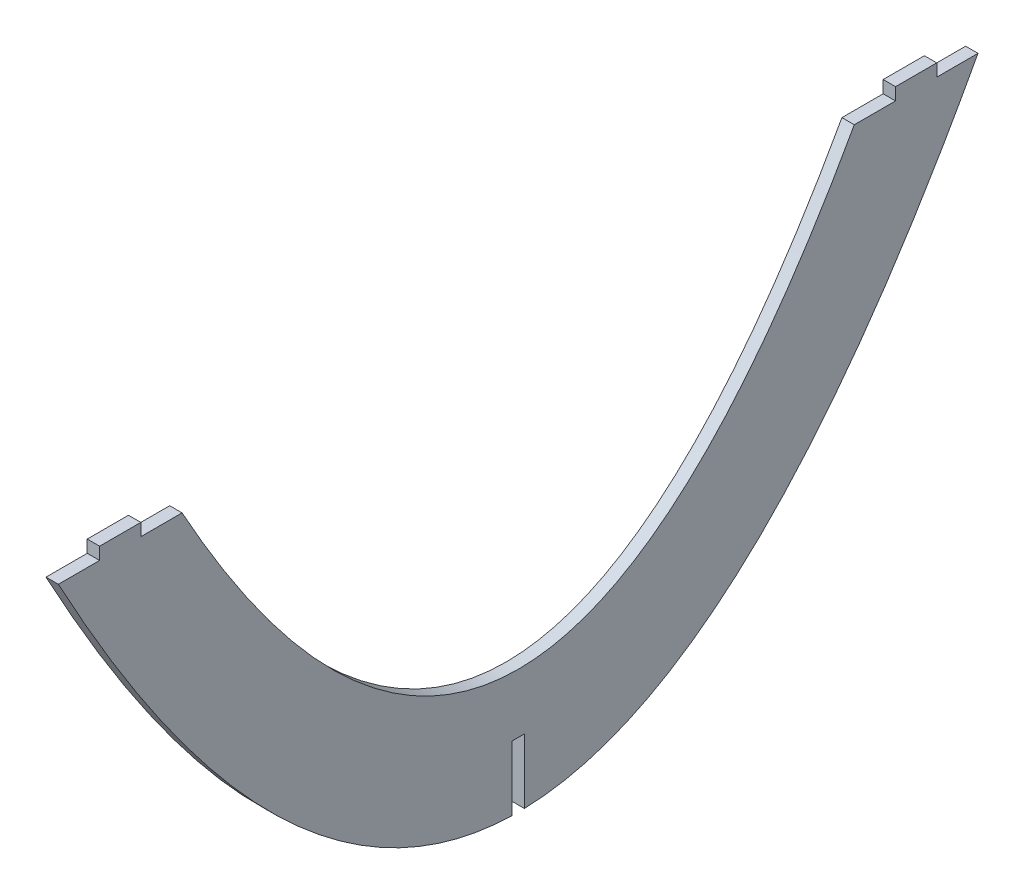
SolidWorks part; units mm, degrees
ref_plane "前视基准面" through (0, 0, 0) normal (0, 0, 1) x (1, 0, 0)
ref_plane "上视基准面" through (0, 0, 0) normal (0, 1, 0) x (1, 0, 0)
ref_plane "右视基准面" through (0, 0, 0) normal (1, 0, 0) x (0, 0, -1)
sketch "草图1" plane through (0, 0, 0) normal (1, 0, 0) x (0, 0, -1)
  line L0 (-111.5128, 119.9959) -> (-81.5105, 119.9959)
  line L1 (81.5105, 119.9959) -> (111.5128, 119.9959)
  spline S0 degree 2 poles (-125.8953, 148.4491) (0, -115.7007) (125.8953, 148.4491) knots 0 0 0 1 1 1 construction
  spline S1 degree 2 poles (-111.5128, 119.9959) (0, -87.2475) (111.5128, 119.9959) knots 0.057121 0.057121 0.057121 0.942879 0.942879 0.942879
  spline S2 degree 2 poles (-124.7834, 218.9152) (0, -126.1669) (124.7834, 218.9152) knots 0 0 0 1 1 1 construction
  spline S3 degree 2 poles (-81.5105, 119.9959) (0, -27.2475) (81.5105, 119.9959) knots 0.173392 0.173392 0.173392 0.826608 0.826608 0.826608
extrude "凸台-拉伸1" add sketch "草图1" along normal blind 3
sketch "草图2" plane through (0, 119.9959, 0) normal (0, 1, 0) x (1, 0, 0)
  line L0 (0, -111.5128) -> (3, -81.5105)
  line L1 (0, 81.5105) -> (3, 111.5128)
  line L2 (0, 111.5128) -> (0, 81.5105) construction
  line L3 (3, 91.5116) -> (0, 91.5116)
  line L4 (3, 91.5116) -> (3, 101.5116)
  line L5 (3, 101.5116) -> (0, 101.5116)
  line L6 (0, 91.5116) -> (0, 101.5116)
  line L7 (3, 91.5116) -> (0, 101.5116) construction
  line L8 (3, 101.5116) -> (0, 91.5116) construction
  line L9 (0, -81.5105) -> (0, -111.5128) construction
  line L10 (3, -101.5116) -> (0, -101.5116)
  line L11 (3, -101.5116) -> (3, -91.5116)
  line L12 (3, -91.5116) -> (0, -91.5116)
  line L13 (0, -101.5116) -> (0, -91.5116)
  line L14 (3, -101.5116) -> (0, -91.5116) construction
  line L15 (3, -91.5116) -> (0, -101.5116) construction
  point P8 (1.5, 96.5116)
  point P15 (1.5, -96.5116)
  line M2 (0, -81.5105) -> (0, -111.5128)
  line M4 (3, -111.5128) -> (3, -81.5105)
extrude "凸台-拉伸2" add sketch "草图2" along normal blind 3 contours L6 L3 L1 L5 | L4 L5 L1 L3 | L0 L12 L10 M2 | L12 L0 L10 M4
sketch "草图3" plane through (0, 0, 0) normal (-1, 0, 0) x (0, 0, 1)
  line L0 (-1.5, 48.1412) -> (-1.5, 32.0685) construction
  line L1 (-1.5, 48.1412) -> (-1.5, 32.0685)
  line L3 (-1.5, 32.0685) -> (1.5, 32.0685)
  line L4 (-1.5, 32.0685) -> (-1.5, 11.0036)
  line L5 (-1.5, 11.0036) -> (1.5, 11.0036)
  line L6 (1.5, 32.0685) -> (1.5, 11.0036)
  spline M7 degree 2 poles (-111.5128, 119.9959) (0, -87.2475) (111.5128, 119.9959) knots 0.057121 0.057121 0.057121 0.942879 0.942879 0.942879
extrude "切除-拉伸1" cut sketch "草图3" against normal through all contours L6 L3 L4 M7
